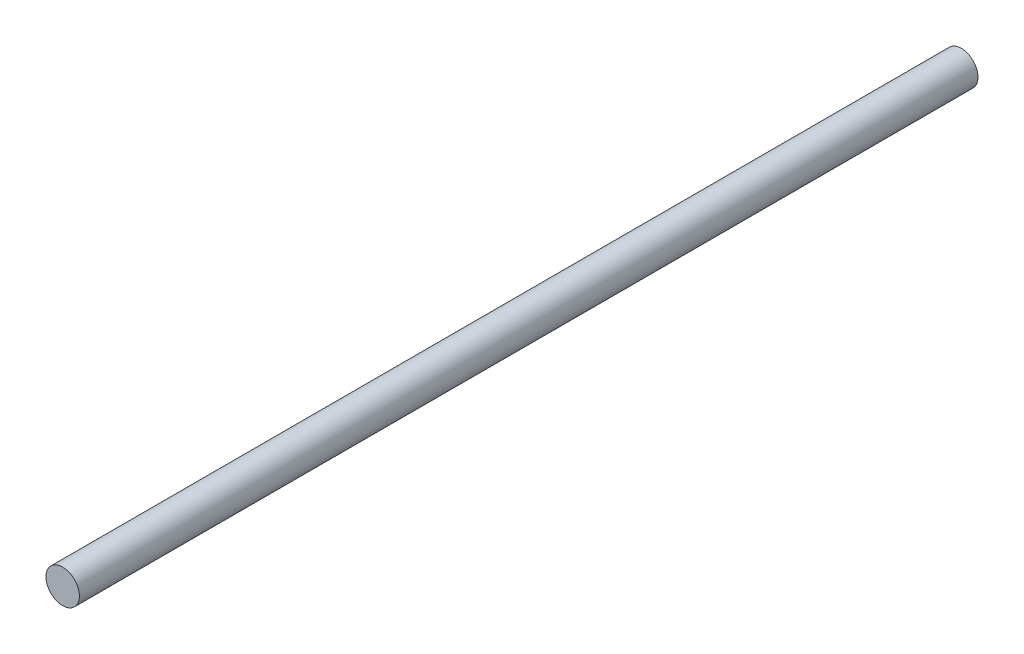
SolidWorks part; units mm, degrees
ref_plane "前基準面" through (0, 0, 0) normal (0, 0, 1) x (1, 0, 0)
ref_plane "上基準面" through (0, 0, 0) normal (0, 1, 0) x (1, 0, 0)
ref_plane "右基準面" through (0, 0, 0) normal (1, 0, 0) x (0, 0, -1)
sketch "草圖1" plane through (0, 0, 0) normal (0, 0, 1) x (1, 0, 0)
  circle A0 centre (0, 0.1657) radius 4
  dimension "D1" = 8
extrude "填料-伸長1" add sketch "草圖1" along normal blind 215
